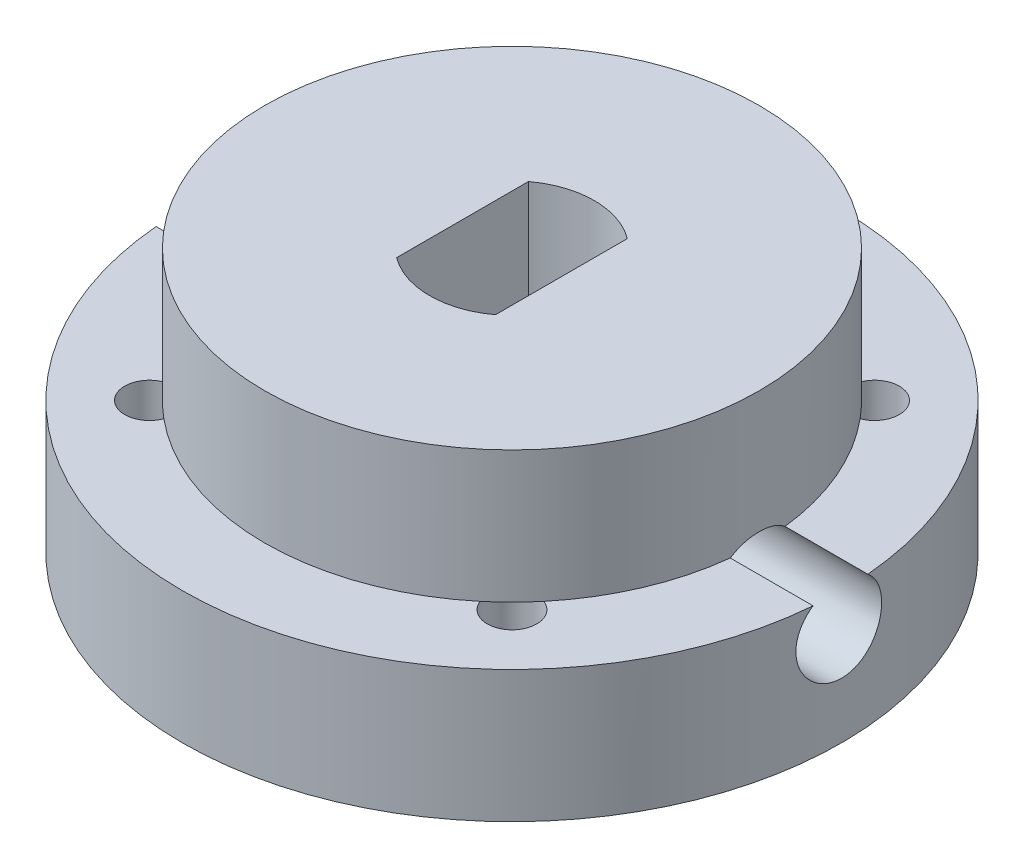
SolidWorks part; units mm, degrees
ref_plane "前视基准面" through (0, 0, 0) normal (0, 0, 1) x (1, 0, 0)
ref_plane "上视基准面" through (0, 0, 0) normal (0, 1, 0) x (1, 0, 0)
ref_plane "右视基准面" through (0, 0, 0) normal (1, 0, 0) x (0, 0, -1)
sketch "草图1" plane through (0, 0, 0) normal (0, 1, 0) x (1, 0, 0)
  line L2 (-1.5, 2) -> (-1.5, -2)
  line L4 (1.5, 2) -> (1.5, -2)
  line L5 (-1.5, 2.8384) -> (1.5, -2.8384) construction
  line L6 (-1.5, -2.8384) -> (1.5, 2.8384) construction
  arc A0 (1.5, 2) -> (-1.5, 2) centre (0, 0) ccw
  circle A1 centre (0, 0) radius 10
  arc A2 (-1.5, -2) -> (1.5, -2) centre (0, 0) ccw
  dimension "D1" = 20
  dimension "D2" = 5
  dimension "D3" = 3
extrude "凸台-拉伸1" add sketch "草图1" along normal blind 8
sketch "草图2" plane through (0, 8, 0) normal (0, 1, 0) x (1, 0, 0)
  circle A0 centre (0, 0) radius 10
  circle A1 centre (0, 0) radius 7.5
  dimension "D1" = 15
extrude "切除-拉伸1" cut sketch "草图2" against normal blind 4
sketch "草图3" plane through (-1.5, 0, 0) normal (1, 0, 0) x (0, 0, -1)
  line L0 (0, 0) -> (0, 3) construction
  circle A0 centre (0, 3) radius 1.3
  dimension "D2" = 2.6
  dimension "D1" = 3
extrude "切除-拉伸2" cut sketch "草图3" against normal through all both and the other way through all
sketch "草图4" plane through (0, 4, 0) normal (0, 1, 0) x (1, 0, 0)
  line L1 (-5.5, 5.5) -> (5.5, 5.5) construction
  line L2 (-5.5, 5.5) -> (-5.5, -5.5) construction
  line L3 (-5.5, -5.5) -> (5.5, -5.5) construction
  line L4 (5.5, 5.5) -> (5.5, -5.5) construction
  line L5 (-5.5, 5.5) -> (5.5, -5.5) construction
  line L6 (-5.5, -5.5) -> (5.5, 5.5) construction
  circle A0 centre (-5.5, 5.5) radius 0.75
  circle A1 centre (5.5, 5.5) radius 0.75
  circle A2 centre (-5.5, -5.5) radius 0.75
  circle A3 centre (5.5, -5.5) radius 0.75
  point P0 (0, 0)
  dimension "D3" = 1.5
  dimension "D4" = 1.5
  dimension "D5" = 1.5
  dimension "D6" = 1.5
  dimension "D1" = 11
  dimension "D2" = 11
extrude "切除-拉伸3" cut sketch "草图4" against normal blind 4
